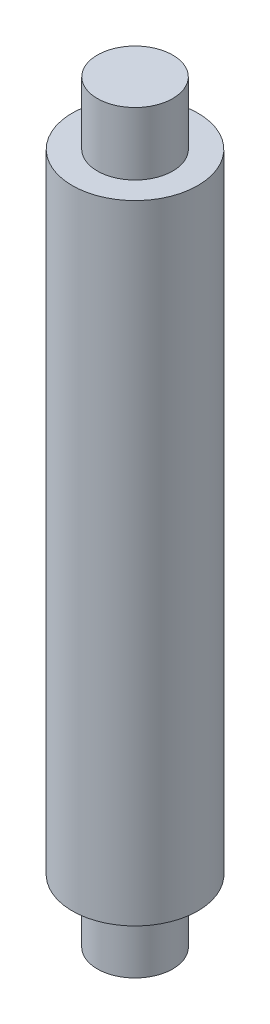
SolidWorks part; units mm, degrees
ref_plane "Front Plane" through (0, 0, 0) normal (0, 0, 1) x (1, 0, 0)
ref_plane "Top Plane" through (0, 0, 0) normal (0, 1, 0) x (1, 0, 0)
ref_plane "Right Plane" through (0, 0, 0) normal (1, 0, 0) x (0, 0, -1)
sketch "Sketch1" plane through (0, 0, 0) normal (0, 0, 1) x (1, 0, 0)
  line L0 (0, 60) -> (-6, 60)
  line L1 (-6, 60) -> (-6, 50)
  line L2 (-6, 50) -> (-10, 50)
  line L3 (-10, 50) -> (-10, -50)
  line L4 (-10, -50) -> (-6, -50)
  line L5 (-6, -50) -> (-6, -60)
  line L6 (-6, -60) -> (0, -60)
  line L7 (0, -60) -> (0, 60)
  point P2 (0, 0)
  point P10 (-10, 0)
  dimension "D1" = 120
  dimension "D2" = 10
  dimension "D3" = 100
  dimension "D4" = 6
revolve "Revolve1" add sketch "Sketch1" angle 360 about L7
